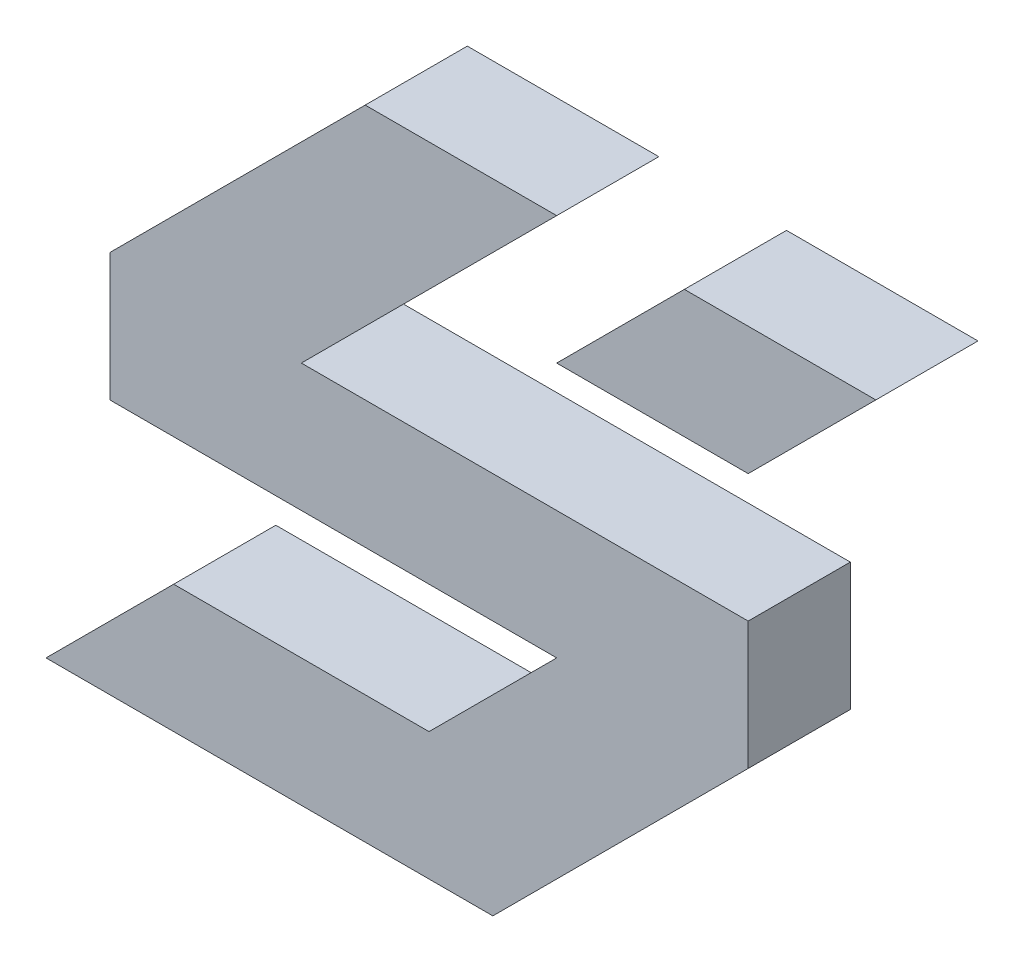
SolidWorks part; units mm, degrees
ref_plane "Front Plane" through (0, 0, 0) normal (0, 0, 1) x (1, 0, 0)
ref_plane "Top Plane" through (0, 0, 0) normal (0, 1, 0) x (1, 0, 0)
ref_plane "Right Plane" through (0, 0, 0) normal (1, 0, 0) x (0, 0, -1)
sketch "Sketch1" plane through (0, 0, 0) normal (0, 0, 1) x (1, 0, 0)
  line L19 (0, 0) -> (75, 0)
  line L20 (0, 0) -> (62.5, 62.5)
  line L21 (75, 0) -> (137.5, 62.5)
  line L22 (62.5, 62.5) -> (137.5, 62.5)
  line L23 (18.75, 0) -> (81.25, 62.5)
  line L24 (37.5, 0) -> (100, 62.5)
  line L25 (56.25, 0) -> (118.75, 62.5)
  line L26 (12.5, 12.5) -> (87.5, 12.5)
  line L27 (25, 25) -> (100, 25)
  line L28 (37.5, 37.5) -> (112.5, 37.5)
  line L29 (50, 50) -> (125, 50)
  line L30 (87.5, 12.5) -> (100, 12.5) construction
  line L31 (100, 25) -> (112.5, 25) construction
  line L32 (100, 25) -> (100, 12.5) construction
  line L33 (125, 37.5) -> (125, 50) construction
  line L34 (112.5, 37.5) -> (112.5, 25) construction
  line L35 (112.5, 37.5) -> (125, 37.5) construction
  line L36 (87.5, 12.5) -> (87.5, 0) construction
  line L37 (87.5, 0) -> (75, 0) construction
  line L38 (100, 25) -> (100, 37.5)
  line L39 (100, 37.5) -> (100, 50) construction
  line L40 (100, 50) -> (112.5, 62.5)
  line L41 (81.25, 50) -> (93.75, 62.5)
  line L42 (87.5, 56.25) -> (106.25, 56.25) construction
  line L43 (75, 56.25) -> (56.25, 56.25) construction
  line L44 (37.5, 37.5) -> (37.5, 25)
  line L45 (43.75, 12.5) -> (31.25, 0)
  point P0 (0, 0)
  dimension "D4" = 45
  dimension "D5" = 75
  dimension "D6" = 62.5
  dimension "D8" = 18.75
  dimension "D9" = 12.5
  dimension "D7" = 4
extrude "Boss-Extrude1" add sketch "Sketch1" along normal blind 10 contours L29 L40 L22 L24 | L41 L29 L24 L22 | L20 L29 L23 L22 | L29 L20 L28 L23 | L28 L44 L27 L23 | L28 L23 L27 L24 | L28 L24 L27 L25 | L27 L38 L28 L25 | L27 L25 L26 L21 | L26 L25 L19 L21 | L26 L24 L19 L25 | L26 L45 L19 L24
equation "\"SIZE\"= 0.5"
equation "\"D5@Sketch1\"=\"SIZE\"*150"
equation "\"D6@Sketch1\"=\"SIZE\"*125"
equation "\"D8@Sketch1\"=(\"SIZE\"*150)/4"
equation "\"D9@Sketch1\"=(\"SIZE\"*125/5)"
